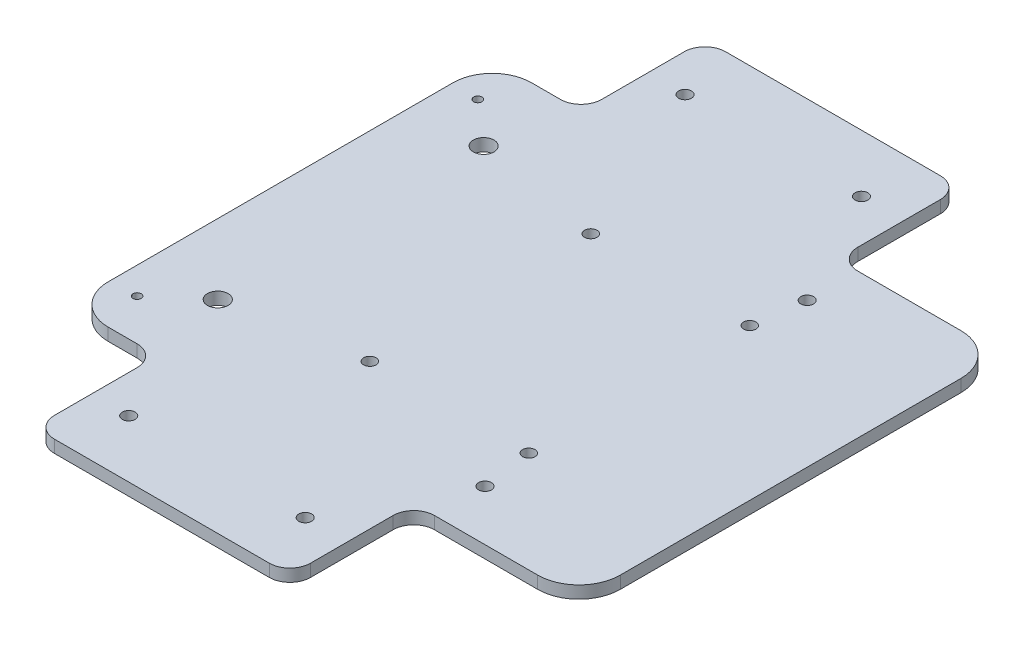
SolidWorks part; units mm, degrees
ref_plane "前视基准面" through (0, 0, 0) normal (0, 0, 1) x (1, 0, 0)
ref_plane "上视基准面" through (0, 0, 0) normal (0, 1, 0) x (1, 0, 0)
ref_plane "右视基准面" through (0, 0, 0) normal (1, 0, 0) x (0, 0, -1)
sketch "草图1" plane through (0, 0, 0) normal (0, 1, 0) x (1, 0, 0)
  line L8 (132, -5) -> (132, -25)
  line L9 (127, -30) -> (75, -30)
  line L10 (70, -25) -> (70, -5)
  line L12 (58, 51.25) -> (172, 51.25) construction
  line L29 (172, 92.5) -> (172, 10)
  line L43 (137, 0) -> (162, 0)
  line L45 (58, 0) -> (65, 0)
  line L46 (127, 132.5) -> (75, 132.5)
  line L47 (70, 127.5) -> (70, 107.5)
  line L49 (132, 107.5) -> (132, 127.5)
  line L50 (65, 102.5) -> (58, 102.5)
  line L54 (48.5, 93) -> (48.5, 9.5)
  line L55 (58, 51.25) -> (48.5, 51.25) construction
  line L56 (137, 102.5) -> (162, 102.5)
  circle A0 centre (96.8555, 24.5) radius 1.5
  circle A1 centre (135.3555, 24.5) radius 1.5
  circle A5 centre (65.4779, 19.0594) radius 2.5
  circle A18 centre (79.0742, -16.0984) radius 1.55
  circle A19 centre (121.8034, -16.0984) radius 1.55
  arc A47 (70, -5) -> (65, 0) centre (65, -5) ccw
  arc A49 (70, -25) -> (75, -30) centre (75, -25) ccw
  arc A51 (127, -30) -> (132, -25) centre (127, -25) ccw
  arc A53 (137, 0) -> (132, -5) centre (137, -5) ccw
  circle A56 centre (135.3555, 78) radius 1.5
  circle A58 centre (96.8555, 78) radius 1.5
  circle A59 centre (65.4779, 83.4406) radius 2.5
  arc A63 (137, 102.5) -> (132, 107.5) centre (137, 107.5) cw
  arc A64 (127, 132.5) -> (132, 127.5) centre (127, 127.5) cw
  arc A65 (70, 127.5) -> (75, 132.5) centre (75, 127.5) cw
  arc A66 (70, 107.5) -> (65, 102.5) centre (65, 107.5) cw
  circle A68 centre (55, 10) radius 1
  circle A69 centre (55, 92.5) radius 1
  arc A73 (58, 102.5) -> (48.5, 93) centre (58, 93) ccw
  arc A74 (58, 0) -> (48.5, 9.5) centre (58, 9.5) cw
  arc A76 (162, 0) -> (172, 10) centre (162, 10) ccw
  arc A77 (162, 102.5) -> (172, 92.5) centre (162, 92.5) cw
  circle A78 centre (121.8034, 118.5984) radius 1.55
  circle A79 centre (79.0742, 118.5984) radius 1.55
  circle A80 centre (137, 90.25) radius 1.55
  circle A81 centre (137, 12.25) radius 1.55
  point P29 (48.5, 51.25)
  dimension "D11" = 26.75
  dimension "D14" = 67.3484
  dimension "D10" = 38.5
  dimension "D15" = 42.7292
  dimension "D16" = 32.1906
  dimension "D17" = 5
  dimension "D3" = 5
  dimension "D2" = 9.5
  dimension "D4" = 25
  dimension "D5" = 39
  dimension "D1" = 30
  dimension "D6" = 5
  dimension "D7" = 35
  dimension "D8" = 5
extrude "凸台-拉伸1" add sketch "草图1" along normal blind 3
